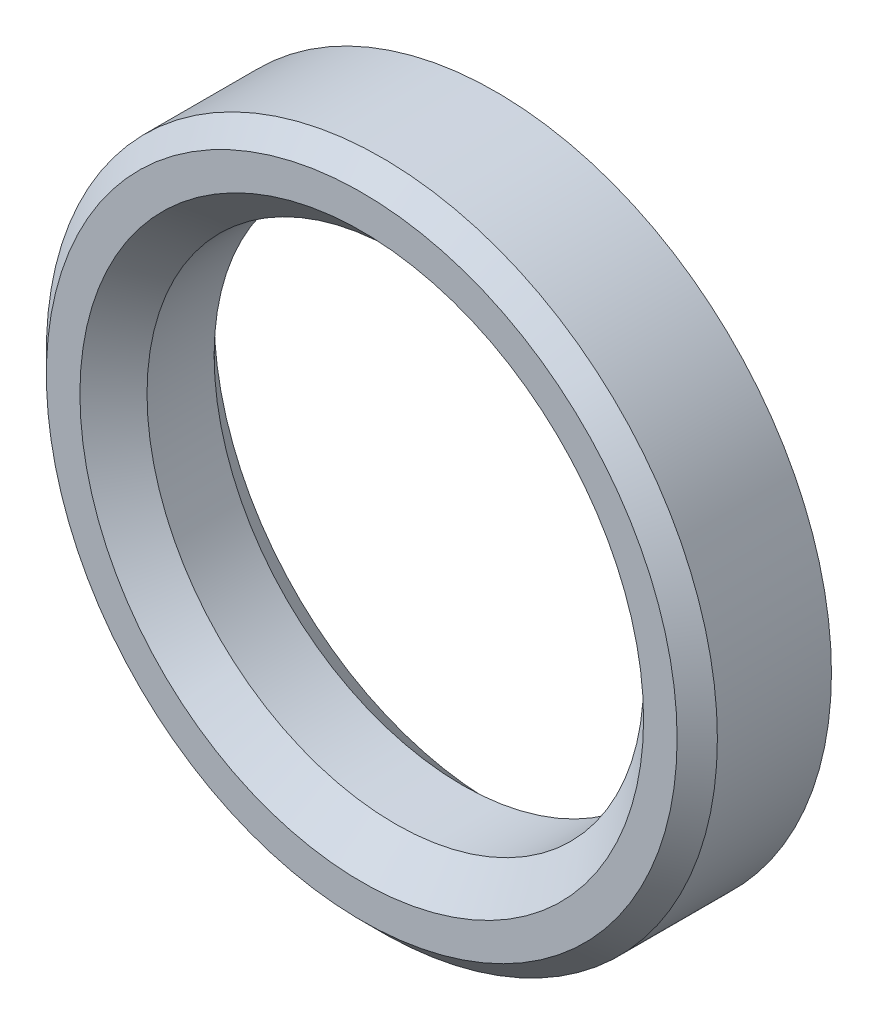
SolidWorks part; units mm, degrees
ref_plane "Front Plane" through (0, 0, 0) normal (0, 0, 1) x (1, 0, 0)
ref_plane "Top Plane" through (0, 0, 0) normal (0, 1, 0) x (1, 0, 0)
ref_plane "Right Plane" through (0, 0, 0) normal (1, 0, 0) x (0, 0, -1)
sketch "Sketch1" plane through (0, 0, 0) normal (0, 0, 1) x (1, 0, 0)
  circle A0 centre (0, 0) radius 5
  circle A1 centre (0, 0) radius 3.7
  dimension "D1" = 10
  dimension "D2" = 7.4
extrude "Boss-Extrude1" add sketch "Sketch1" along normal blind 2
chamfer "Chamfer1" distance 0.3 angle 45 1 edges at (5, 0, 2)
chamfer "Chamfer2" distance 0.5 angle 45 2 edges at (3.7, 0, 2) (3.7, 0, 0)
